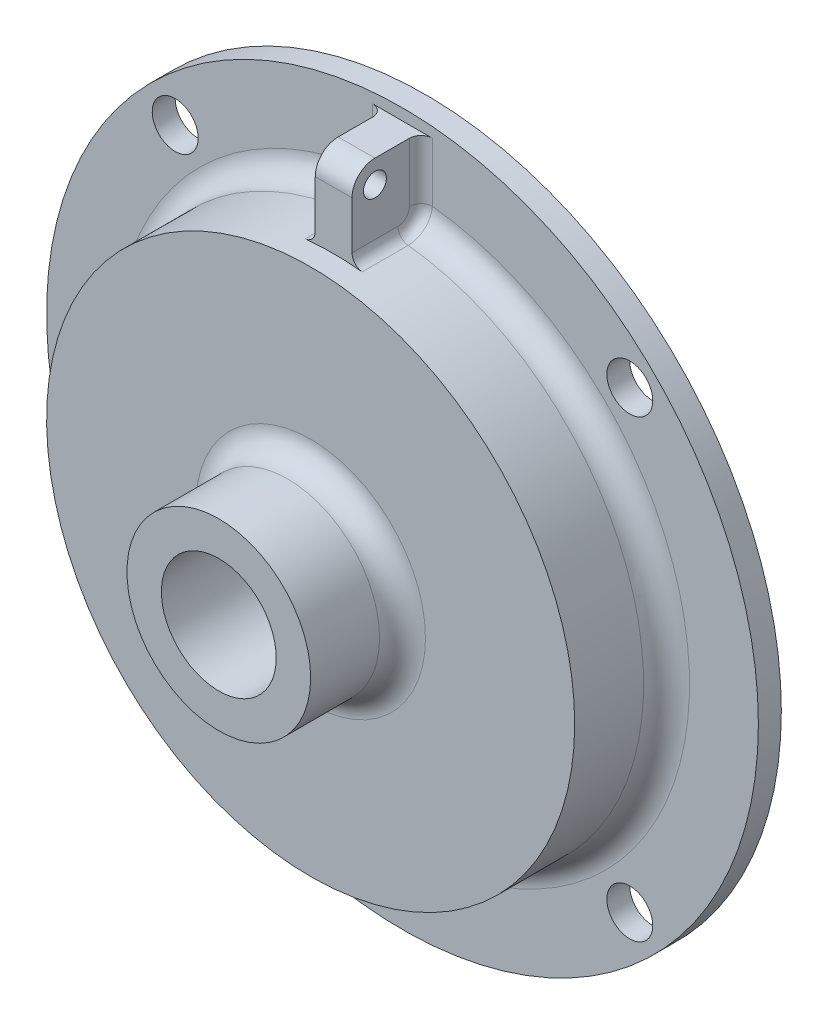
SolidWorks part; units mm, degrees
material "PW40:6:Sc:0:Re:24:"
ref_plane "Front" through (0, 0, 0) normal (0, 0, 1) x (1, 0, 0)
ref_plane "Top" through (0, 0, 0) normal (0, 1, 0) x (1, 0, 0)
ref_plane "Right" through (0, 0, 0) normal (1, 0, 0) x (0, 0, -1)
sketch "Sketch1" plane through (0, 0, 0) normal (0, 0, 1) x (1, 0, 0)
  circle A0 centre (0, 0) radius 49.2125
  dimension "D1" = 98.425
extrude "Base-Extrude" add sketch "Sketch1" along normal blind 3.175
sketch "Sketch5" plane through (0, 0, 3.175) normal (0, 0, 1) x (1, 0, 0)
  line L0 (31.4309, 31.4309) -> (0, 0) construction
  line L1 (0, 0) -> (44.45, 0) construction
  circle A0 centre (0, 0) radius 44.45 construction
  circle A1 centre (31.4309, 31.4309) radius 3.175
  dimension "D1" = 88.9
  dimension "D2" = 6.35
  dimension "D3" = 45
extrude "Cut-Extrude2" cut sketch "Sketch5" against normal through all
pattern_circular "CirPattern1" count 4 every 90 about axis through (0, 0, 0) along (0, 0, 1) of "Cut-Extrude2"
sketch "Sketch2" plane through (0, 0, 3.175) normal (0, 0, 1) x (1, 0, 0)
  circle A0 centre (0, 0) radius 36.5125
  dimension "D1" = 73.025
extrude "Boss-Extrude1" add sketch "Sketch2" along normal blind 12.7
sketch "Sketch3" plane through (0, 0, 15.875) normal (0, 0, 1) x (1, 0, 0)
  circle A0 centre (0, 0) radius 12.7
  dimension "D1" = 25.4
extrude "Boss-Extrude2" add sketch "Sketch3" along normal blind 12.7
fillet "Fillet1" radius 3.175 2 edges at (36.5125, 0, 3.175) (12.7, 0, 15.875)
sketch "Sketch6" plane through (0, 0, 0) normal (0, 1, 0) x (1, 0, 0)
  line L0 (-2.54, -3.175) -> (-2.54, -12.7)
  line L1 (-39.6875, -3.175) -> (39.6875, -3.175) construction
  line L2 (-2.54, -3.175) -> (2.54, -3.175)
  line L3 (-49.2125, -3.175) -> (49.2125, -3.175) construction
  line L4 (2.54, -3.175) -> (2.54, -12.7)
  line L5 (-2.54, -12.7) -> (2.54, -12.7)
  line L6 (0, 0) -> (0, -38.11) construction
  line L7 (0, -3.175) -> (0, 0) construction
  dimension "D1" = 5.08
  dimension "D2" = 9.525
extrude "Boss-Extrude3" add sketch "Sketch6" along normal blind 47.625
sketch "Sketch4" plane through (0, 0, 28.575) normal (0, 0, 1) x (1, 0, 0)
  circle A0 centre (0, 0) radius 7.9375
  dimension "D1" = 15.875
extrude "Cut-Extrude1" cut sketch "Sketch4" against normal through all
fillet "Fillet2" radius 3.175 1 edges at (0, 47.625, 12.7)
sketch "Sketch7" plane through (2.54, 0, 0) normal (1, 0, 0) x (0, 0, -1)
  circle A0 centre (-9.525, 44.45) radius 1.5875
  arc A1 (-9.525, 47.625) -> (-12.7, 44.45) centre (-9.525, 44.45) ccw construction
  dimension "D1" = 3.175
extrude "Cut-Extrude3" cut sketch "Sketch7" against normal up to next
fillet "Fillet3" radius 1.5875 6 edges at (2.54, 41.6917, 8.7475) (-2.54, 41.6917, 8.7475) (2.54, 43.6156, 3.175) (-2.54, 36.424, 9.525) (-2.54, 43.6156, 3.175) (2.54, 36.424, 9.525)
